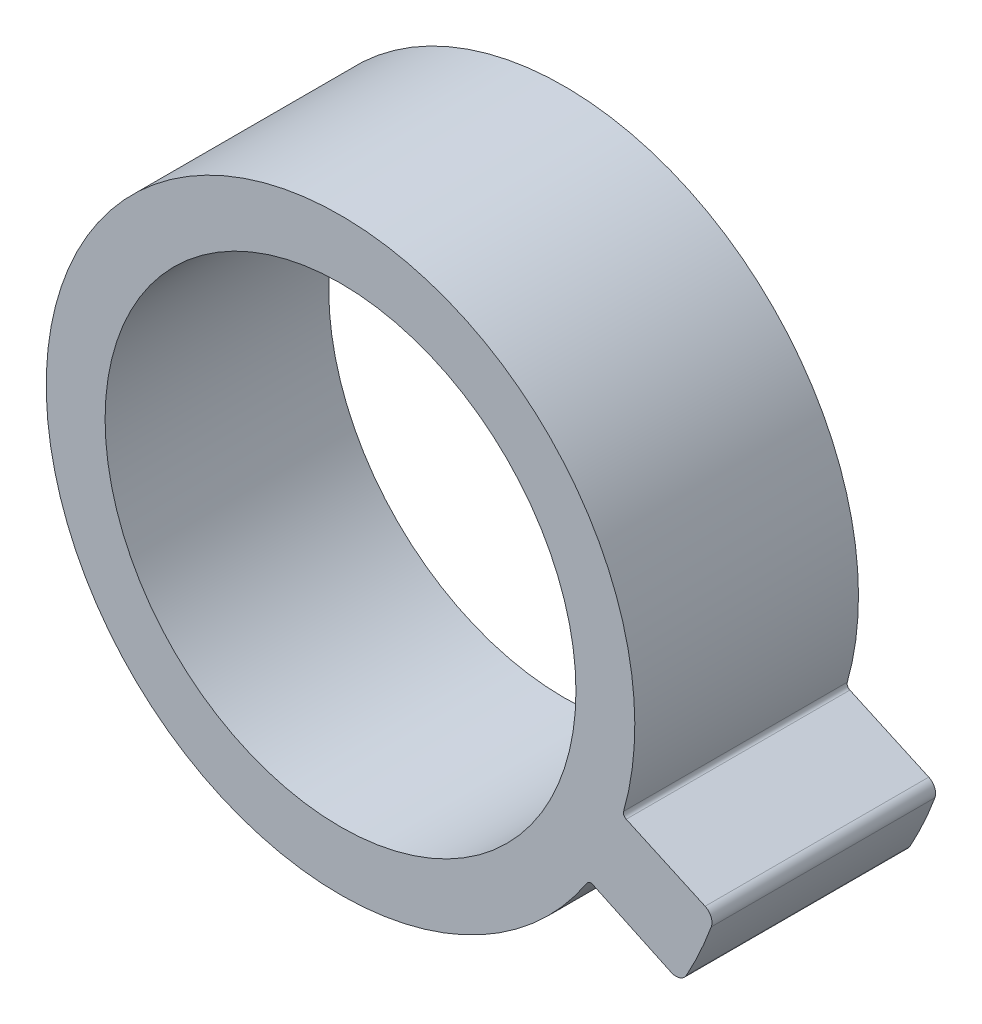
SolidWorks part; units mm, degrees
material "Chêne"
ref_plane "Plan de face" through (0, 0, 0) normal (0, 0, 1) x (1, 0, 0)
ref_plane "Plan de dessus" through (0, 0, 0) normal (0, 1, 0) x (1, 0, 0)
ref_plane "Plan de droite" through (0, 0, 0) normal (1, 0, 0) x (0, 0, -1)
sketch "Esquisse1" plane through (0, 0, 0) normal (0, 0, 1) x (1, 0, 0)
  line L0 (15.4852, -5.1767) -> (12.1342, -3.6507)
  line L1 (14.0407, -8.3254) -> (10.7168, -6.7654)
  arc A0 (12.0247, -3.4141) -> (10.4644, -6.8371) centre (0, 0) ccw
  arc A1 (15.7471, -5.8046) -> (14.6908, -8.1145) centre (0, 0) cw
  arc A2 (15.7471, -5.8046) -> (15.4852, -5.1767) centre (15.278, -5.6317) ccw
  arc A3 (14.0407, -8.3254) -> (14.6908, -8.1145) centre (14.2532, -7.8727) ccw
  circle A4 centre (0, 0) radius 10
  arc A5 (12.1342, -3.6507) -> (12.0247, -3.4141) centre (12.2171, -3.4687) cw
  arc A6 (10.7168, -6.7654) -> (10.4644, -6.8371) centre (10.6319, -6.9465) ccw
  point P116 (0, 0)
  point P374 (0, 0)
extrude "Boss.-Extru.3" add sketch "Esquisse1" along normal blind 9.5
